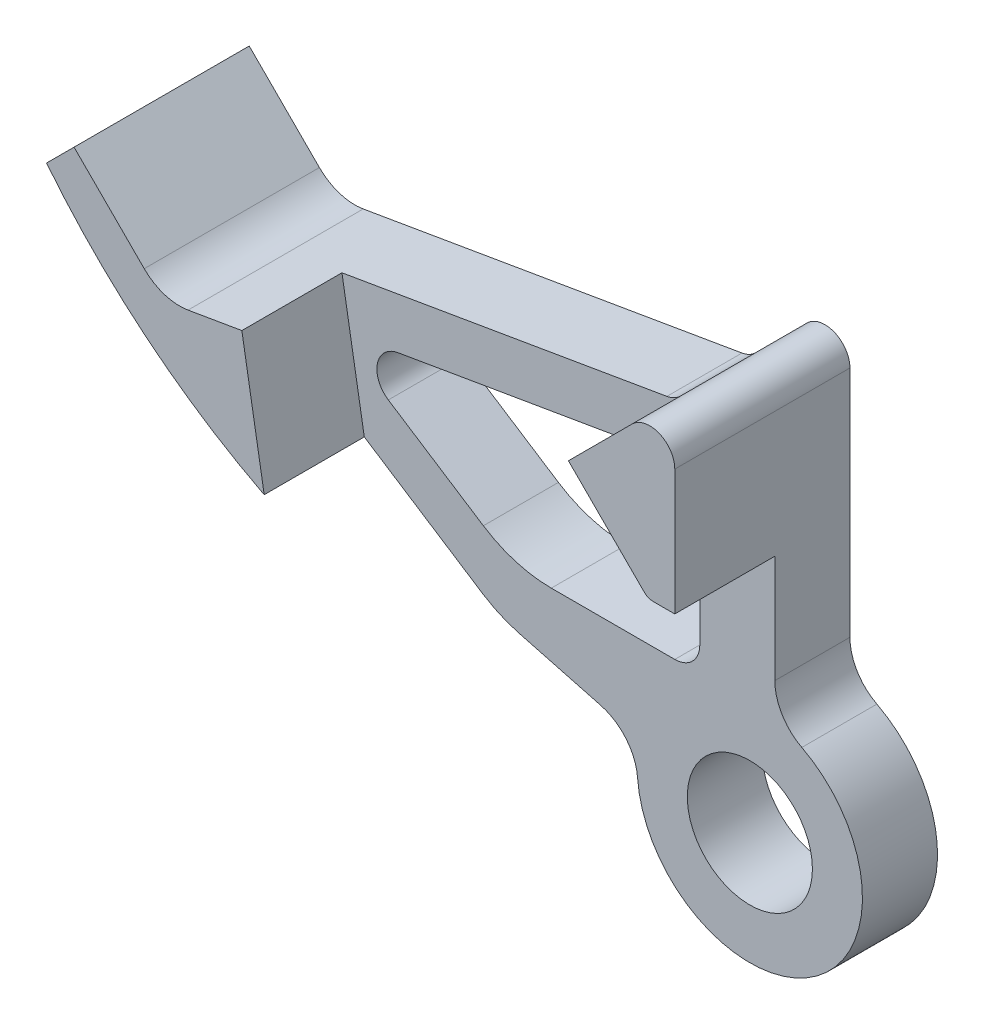
SolidWorks part; units mm, degrees
ref_plane "Plan1" through (0, 0, 0) normal (0, 0, 1) x (1, 0, 0)
ref_plane "Plan2" through (0, 0, 0) normal (0, 1, 0) x (1, 0, 0)
ref_plane "Plan3" through (0, 0, 0) normal (1, 0, 0) x (0, 0, -1)
sketch "Esquisse1" plane through (0, 0, 0) normal (0, 0, 1) x (1, 0, 0)
  line L0 (-10.6678, 2.9318) -> (-19.8443, 8.8649)
  line L1 (-9.2312, 2.2967) -> (-5.9695, 1.4342)
  line L2 (1, 5.7663) -> (1, 15.0858)
  line L4 (-2, 9.1532) -> (-2, 5.5)
  line L5 (-0.7071, 15.7929) -> (-2.7749, 13.7251)
  line L6 (-19.4695, 10.6905) -> (-3.3138, 13.4465)
  line L9 (-14.072, 9.5823) -> (-4.3767, 11.2363)
  line L10 (-10.6489, 5.3012) -> (-14.4468, 7.7568)
  line L11 (-3, 4.5) -> (-7.9341, 4.5)
  line L12 (-2.1595, 9.9448) -> (-2.1192, 9.8333)
  circle A0 centre (0, 0) radius 2.5
  arc A1 (-4.4867, -0.3457) -> (2.0769, 3.992) centre (0, 0) ccw
  arc A2 (-5.9695, 1.4342) -> (-4.4867, -0.3457) centre (-6.4808, -0.4993) cw
  arc A3 (1, 5.7663) -> (2.0769, 3.992) centre (3, 5.7663) ccw
  arc A4 (-2.1192, 9.8333) -> (-2, 9.1532) centre (-4, 9.1532) cw
  arc A5 (-4.3767, 11.2363) -> (-2.1595, 9.9448) centre (-4.0403, 9.2647) cw
  arc A6 (-10.6678, 2.9318) -> (-9.2312, 2.2967) centre (-7.953, 7.1306) ccw
  arc A7 (-10.6489, 5.3012) -> (-7.9341, 4.5) centre (-7.9341, 9.5) ccw
  arc A8 (-14.072, 9.5823) -> (-14.4468, 7.7568) centre (-13.9039, 8.5966) ccw
  arc A9 (-3, 4.5) -> (-2, 5.5) centre (-3, 5.5) ccw
  arc A10 (-19.4695, 10.6905) -> (-19.8443, 8.8649) centre (-19.3013, 9.7047) ccw
  arc A11 (1, 15.0858) -> (-0.7071, 15.7929) centre (0, 15.0858) ccw
  arc A12 (-3.3138, 13.4465) -> (-2.7749, 13.7251) centre (-3.482, 14.4322) ccw
  point P32 (-22, 10.2588)
  point P35 (1, 17.5)
  dimension "D1" = 5
  dimension "D2" = 9
  dimension "D7" = 2
  dimension "D8" = 5
  dimension "D9" = 1
  dimension "D3" = 2
  dimension "D4" = 17.5
  dimension "D6" = 45
  dimension "D11" = 22
  dimension "D5" = 3
extrude "Base-Extrusion" add sketch "Esquisse1" along normal blind 3
sketch "Esquisse2" plane through (0, 0, 0) normal (0, 0, -1) x (-1, 0, 0)
  line L0 (0.7071, 15.7929) -> (3.25, 13.25)
  line L1 (0.7071, 15.7929) -> (2.7749, 13.7251) construction
  line L2 (-1, 15.0858) -> (-1, 10.0721)
  line L3 (-1, 10.0721) -> (-0.135, 10.0721)
  line L5 (19.8443, 8.8649) -> (10.6678, 2.9318) construction
  line L7 (0.2186, 10.2186) -> (3.25, 13.25)
  line L8 (16.3, 11.2311) -> (15.4069, 5.9959)
  line L9 (3.3138, 13.4465) -> (19.4695, 10.6905) construction
  line L10 (16.3, 11.2311) -> (18.4501, 10.8643)
  line L11 (20.2006, 11.4217) -> (23.005, 14.226)
  line L12 (0, 0) -> (30, 0) construction
  line L13 (23.005, 14.226) -> (24.1051, 13.1258)
  arc A0 (0.7071, 15.7929) -> (-1, 15.0858) centre (0, 15.0858) ccw
  arc A1 (0.2186, 10.2186) -> (-0.135, 10.0721) centre (-0.135, 10.5721) cw
  arc A2 (20.2006, 11.4217) -> (18.4501, 10.8643) centre (18.7864, 12.8359) cw
  arc A4 (24.1051, 13.1258) -> (15.4069, 5.9959) centre (3.1056, 29.8738) cw
  point P27 (19.4695, 10.6905)
  point P30 (19.8443, 8.8649)
  dimension "D2" = 1
  dimension "D3" = 0.5
  dimension "D7" = 2
  dimension "D1" = 45
  dimension "D5" = 5
  dimension "D6" = 16.3
extrude "Boss.-Extru.1" add sketch "Esquisse2" against normal blind 7
